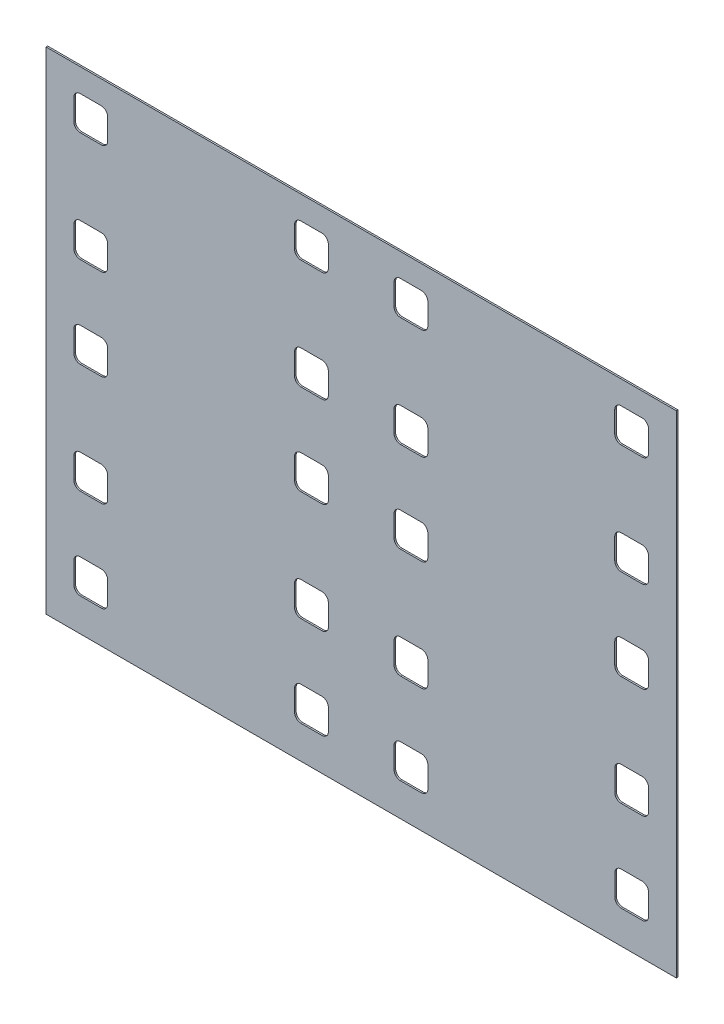
SolidWorks part; units mm, degrees
material "ABS"
ref_plane "X-Y Datum" through (0, 0, 0) normal (0, 0, 1) x (1, 0, 0)
ref_plane "X-Z Datum" through (0, 0, 0) normal (0, 1, 0) x (1, 0, 0)
ref_plane "Y-Z Datum" through (0, 0, 0) normal (1, 0, 0) x (0, 0, -1)
sketch "Sketch9" plane through (0, 0, 0) normal (0, 0, 1) x (1, 0, 0)
  line L0 (-83.6449, -183.2879) -> (-83.647, -162.6379) construction
  line L1 (-89.9977, -156.2885) -> (-110.6477, -156.2907) construction
  line L2 (-116.997, -162.6414) -> (-116.9949, -183.2914) construction
  line L3 (-110.6442, -189.6407) -> (-89.9942, -189.6385) construction
  line L4 (476.934, -311.4483) -> (476.8831, 172.8027)
  line L5 (476.8831, 172.8027) -> (-144.3755, 172.7375)
  line L6 (-144.3755, 172.7375) -> (-144.3246, -311.5135)
  line L7 (-144.3246, -311.5135) -> (476.934, -311.4483)
  line L8 (476.934, -311.4483) -> (476.8831, 172.8027)
  line L9 (476.8831, 172.8027) -> (-144.3755, 172.7375)
  line L10 (-144.3755, 172.7375) -> (-144.3246, -311.5135)
  line L11 (-144.3246, -311.5135) -> (476.934, -311.4483)
  line L12 (-110.6556, -81.3351) -> (-90.0056, -81.3329) construction
  line L13 (-83.6562, -74.9823) -> (-83.6584, -54.3323) construction
  line L14 (-90.0091, -47.9829) -> (-110.6591, -47.9851) construction
  line L15 (-117.0084, -54.3358) -> (-117.0062, -74.9858) construction
  line L16 (-83.677, 122.7313) -> (-83.6792, 143.3813) construction
  line L17 (-90.0298, 149.7307) -> (-110.6798, 149.7285) construction
  line L18 (-117.0292, 143.3778) -> (-117.027, 122.7278) construction
  line L19 (-110.6763, 116.3785) -> (-90.0263, 116.3807) construction
  line L20 (-110.665, 8.0729) -> (-90.015, 8.0751) construction
  line L21 (-117.0178, 35.0722) -> (-117.0156, 14.4222) construction
  line L22 (-90.0185, 41.4251) -> (-110.6685, 41.4229) construction
  line L23 (-83.6656, 14.4257) -> (-83.6678, 35.0757) construction
  line L24 (-83.6449, -183.2879) -> (-83.647, -162.6379)
  line L25 (-89.9977, -156.2885) -> (-110.6477, -156.2907)
  line L26 (-116.997, -162.6414) -> (-116.9949, -183.2914)
  line L27 (-110.6442, -189.6407) -> (-89.9942, -189.6385)
  line L28 (-110.6556, -81.3351) -> (-90.0056, -81.3329)
  line L29 (-83.6562, -74.9823) -> (-83.6584, -54.3323)
  line L30 (-90.0091, -47.9829) -> (-110.6591, -47.9851)
  line L31 (-117.0084, -54.3358) -> (-117.0062, -74.9858)
  line L32 (-83.677, 122.7313) -> (-83.6792, 143.3813)
  line L33 (-90.0298, 149.7307) -> (-110.6798, 149.7285)
  line L34 (-117.0292, 143.3778) -> (-117.027, 122.7278)
  line L35 (-110.6763, 116.3785) -> (-90.0263, 116.3807)
  line L36 (-110.665, 8.0729) -> (-90.015, 8.0751)
  line L37 (-117.0178, 35.0722) -> (-117.0156, 14.4222)
  line L38 (-90.0185, 41.4251) -> (-110.6685, 41.4229)
  line L39 (-83.6656, 14.4257) -> (-83.6678, 35.0757)
  line L40 (-83.6355, -272.6959) -> (-83.6376, -252.0459) construction
  line L41 (-89.9883, -245.6965) -> (-110.6383, -245.6987) construction
  line L42 (-116.9876, -252.0494) -> (-116.9855, -272.6994) construction
  line L43 (-110.6348, -279.0487) -> (-89.9848, -279.0465) construction
  line L44 (-83.6355, -272.6959) -> (-83.6376, -252.0459)
  line L45 (-89.9883, -245.6965) -> (-110.6383, -245.6987)
  line L46 (-116.9876, -252.0494) -> (-116.9855, -272.6994)
  line L47 (-110.6348, -279.0487) -> (-89.9848, -279.0465)
  arc A0 (-89.9942, -189.6385) -> (-83.6449, -183.2879) centre (-89.9949, -183.2885) ccw construction
  arc A1 (-83.647, -162.6379) -> (-89.9977, -156.2885) centre (-89.997, -162.6385) ccw construction
  arc A2 (-110.6477, -156.2907) -> (-116.997, -162.6414) centre (-110.647, -162.6407) ccw construction
  arc A3 (-116.9949, -183.2914) -> (-110.6442, -189.6407) centre (-110.6449, -183.2907) ccw construction
  arc A4 (-90.0056, -81.3329) -> (-83.6562, -74.9823) centre (-90.0062, -74.9829) ccw construction
  arc A5 (-83.6584, -54.3323) -> (-90.0091, -47.9829) centre (-90.0084, -54.3329) ccw construction
  arc A6 (-110.6591, -47.9851) -> (-117.0084, -54.3358) centre (-110.6584, -54.3351) ccw construction
  arc A7 (-117.0062, -74.9858) -> (-110.6556, -81.3351) centre (-110.6562, -74.9851) ccw construction
  arc A8 (-90.0263, 116.3807) -> (-83.677, 122.7313) centre (-90.027, 122.7307) ccw construction
  arc A9 (-83.6792, 143.3813) -> (-90.0298, 149.7307) centre (-90.0292, 143.3807) ccw construction
  arc A10 (-110.6798, 149.7285) -> (-117.0292, 143.3778) centre (-110.6792, 143.3785) ccw construction
  arc A11 (-117.027, 122.7278) -> (-110.6763, 116.3785) centre (-110.677, 122.7285) ccw construction
  arc A12 (-83.6678, 35.0757) -> (-90.0185, 41.4251) centre (-90.0178, 35.0751) ccw construction
  arc A13 (-90.015, 8.0751) -> (-83.6656, 14.4257) centre (-90.0156, 14.4251) ccw construction
  arc A14 (-117.0156, 14.4222) -> (-110.665, 8.0729) centre (-110.6656, 14.4229) ccw construction
  arc A15 (-110.6685, 41.4229) -> (-117.0178, 35.0722) centre (-110.6678, 35.0729) ccw construction
  arc A16 (-89.9942, -189.6385) -> (-83.6449, -183.2879) centre (-89.9949, -183.2885) ccw
  arc A17 (-83.647, -162.6379) -> (-89.9977, -156.2885) centre (-89.997, -162.6385) ccw
  arc A18 (-110.6477, -156.2907) -> (-116.997, -162.6414) centre (-110.647, -162.6407) ccw
  arc A19 (-116.9949, -183.2914) -> (-110.6442, -189.6407) centre (-110.6449, -183.2907) ccw
  arc A20 (-90.0056, -81.3329) -> (-83.6562, -74.9823) centre (-90.0062, -74.9829) ccw
  arc A21 (-83.6584, -54.3323) -> (-90.0091, -47.9829) centre (-90.0084, -54.3329) ccw
  arc A22 (-110.6591, -47.9851) -> (-117.0084, -54.3358) centre (-110.6584, -54.3351) ccw
  arc A23 (-117.0062, -74.9858) -> (-110.6556, -81.3351) centre (-110.6562, -74.9851) ccw
  arc A24 (-90.0263, 116.3807) -> (-83.677, 122.7313) centre (-90.027, 122.7307) ccw
  arc A25 (-83.6792, 143.3813) -> (-90.0298, 149.7307) centre (-90.0292, 143.3807) ccw
  arc A26 (-110.6798, 149.7285) -> (-117.0292, 143.3778) centre (-110.6792, 143.3785) ccw
  arc A27 (-117.027, 122.7278) -> (-110.6763, 116.3785) centre (-110.677, 122.7285) ccw
  arc A28 (-83.6678, 35.0757) -> (-90.0185, 41.4251) centre (-90.0178, 35.0751) ccw
  arc A29 (-90.015, 8.0751) -> (-83.6656, 14.4257) centre (-90.0156, 14.4251) ccw
  arc A30 (-117.0156, 14.4222) -> (-110.665, 8.0729) centre (-110.6656, 14.4229) ccw
  arc A31 (-110.6685, 41.4229) -> (-117.0178, 35.0722) centre (-110.6678, 35.0729) ccw
  arc A32 (-89.9848, -279.0465) -> (-83.6355, -272.6959) centre (-89.9855, -272.6965) ccw construction
  arc A33 (-110.6383, -245.6987) -> (-116.9876, -252.0494) centre (-110.6376, -252.0487) ccw construction
  arc A34 (-116.9855, -272.6994) -> (-110.6348, -279.0487) centre (-110.6355, -272.6987) ccw construction
  arc A35 (-89.9848, -279.0465) -> (-83.6355, -272.6959) centre (-89.9855, -272.6965) ccw
  arc A36 (-110.6383, -245.6987) -> (-116.9876, -252.0494) centre (-110.6376, -252.0487) ccw
  arc A37 (-116.9855, -272.6994) -> (-110.6348, -279.0487) centre (-110.6355, -272.6987) ccw
  arc A38 (-83.6376, -252.0459) -> (-89.9883, -245.6965) centre (-89.9876, -252.0465) ccw construction
  arc A39 (-83.6376, -252.0459) -> (-89.9883, -245.6965) centre (-89.9876, -252.0465) ccw
  dimension "D1" = 0
extrude "Boss-Extrude2" add sketch "Sketch9" along normal blind 1.5875 contours L10 L11 L8 L9 A39 L44 A35 L47 A37 L46 A36 L45 A31 L38 A28 L39 A29 L36 A30 L37 A27 L34 A26 L33 A25 L32 A24 L35 A23 L31 A22 L30 A21 L29 A20 L28 A19 L26 A18 L25 A17 L24 A16 L27 | L44 A39 L45 A36 L46 A37 L47 A35 | L26 A19 L27 A16 L24 A17 L25 A18 | L38 A31 L37 A30 L36 A29 L39 A28 | L34 A27 L35 A24 L32 A25 L33 A26 | L31 A23 L28 A20 L29 A21 L30 A22
sketch "Sketch10" plane through (0, 0, 1.5875) normal (0, 0, 1) x (1, 0, 0)
  line L4 (476.934, -311.4483) -> (476.8831, 172.8027)
  line L5 (476.8831, 172.8027) -> (-144.3755, 172.7375)
  line L6 (-144.3755, 172.7375) -> (-144.3246, -311.5135)
  line L7 (-144.3246, -311.5135) -> (476.934, -311.4483)
  line L8 (476.934, -311.4483) -> (476.8831, 172.8027)
  line L9 (476.8831, 172.8027) -> (-144.3755, 172.7375)
  line L10 (-144.3755, 172.7375) -> (-144.3246, -311.5135)
  line L11 (-144.3246, -311.5135) -> (476.934, -311.4483)
  line L12 (-116.997, -162.6414) -> (-116.9949, -183.2914)
  line L13 (-110.6442, -189.6407) -> (-89.9942, -189.6385)
  line L14 (-83.6449, -183.2879) -> (-83.647, -162.6379)
  line L15 (-89.9977, -156.2885) -> (-110.6477, -156.2907)
  line L16 (-116.997, -162.6414) -> (-116.9949, -183.2914)
  line L17 (-110.6442, -189.6407) -> (-89.9942, -189.6385)
  line L18 (-83.6449, -183.2879) -> (-83.647, -162.6379)
  line L19 (-89.9977, -156.2885) -> (-110.6477, -156.2907)
  line L20 (-116.9876, -252.0494) -> (-116.9855, -272.6994)
  line L21 (-89.9883, -245.6965) -> (-110.6383, -245.6987)
  line L22 (-83.6355, -272.6959) -> (-83.6376, -252.0459)
  line L23 (-110.6348, -279.0487) -> (-89.9848, -279.0465)
  line L24 (-116.9876, -252.0494) -> (-116.9855, -272.6994)
  line L25 (-89.9883, -245.6965) -> (-110.6383, -245.6987)
  line L26 (-83.6355, -272.6959) -> (-83.6376, -252.0459)
  line L27 (-110.6348, -279.0487) -> (-89.9848, -279.0465)
  line L28 (-90.0091, -47.9829) -> (-110.6591, -47.9851)
  line L29 (-117.0084, -54.3358) -> (-117.0062, -74.9858)
  line L30 (-110.6556, -81.3351) -> (-90.0056, -81.3329)
  line L31 (-83.6562, -74.9823) -> (-83.6584, -54.3323)
  line L32 (-90.0091, -47.9829) -> (-110.6591, -47.9851)
  line L33 (-117.0084, -54.3358) -> (-117.0062, -74.9858)
  line L34 (-110.6556, -81.3351) -> (-90.0056, -81.3329)
  line L35 (-83.6562, -74.9823) -> (-83.6584, -54.3323)
  line L36 (-83.677, 122.7313) -> (-83.6792, 143.3813)
  line L37 (-110.6763, 116.3785) -> (-90.0263, 116.3807)
  line L38 (-117.0292, 143.3778) -> (-117.027, 122.7278)
  line L39 (-90.0298, 149.7307) -> (-110.6798, 149.7285)
  line L40 (-83.677, 122.7313) -> (-83.6792, 143.3813)
  line L41 (-110.6763, 116.3785) -> (-90.0263, 116.3807)
  line L42 (-117.0292, 143.3778) -> (-117.027, 122.7278)
  line L43 (-90.0298, 149.7307) -> (-110.6798, 149.7285)
  line L44 (-110.665, 8.0729) -> (-90.015, 8.0751)
  line L45 (-83.6656, 14.4257) -> (-83.6678, 35.0757)
  line L46 (-90.0185, 41.4251) -> (-110.6685, 41.4229)
  line L47 (-117.0178, 35.0722) -> (-117.0156, 14.4222)
  line L48 (-110.665, 8.0729) -> (-90.015, 8.0751)
  line L49 (-83.6656, 14.4257) -> (-83.6678, 35.0757)
  line L50 (-90.0185, 41.4251) -> (-110.6685, 41.4229)
  line L51 (-117.0178, 35.0722) -> (-117.0156, 14.4222)
  arc A4 (-116.9949, -183.2914) -> (-110.6442, -189.6407) centre (-110.6449, -183.2907) ccw
  arc A5 (-89.9942, -189.6385) -> (-83.6449, -183.2879) centre (-89.9949, -183.2885) ccw
  arc A6 (-83.647, -162.6379) -> (-89.9977, -156.2885) centre (-89.997, -162.6385) ccw
  arc A7 (-110.6477, -156.2907) -> (-116.997, -162.6414) centre (-110.647, -162.6407) ccw
  arc A8 (-116.9949, -183.2914) -> (-110.6442, -189.6407) centre (-110.6449, -183.2907) ccw
  arc A9 (-89.9942, -189.6385) -> (-83.6449, -183.2879) centre (-89.9949, -183.2885) ccw
  arc A10 (-83.647, -162.6379) -> (-89.9977, -156.2885) centre (-89.997, -162.6385) ccw
  arc A11 (-110.6477, -156.2907) -> (-116.997, -162.6414) centre (-110.647, -162.6407) ccw
  arc A12 (-110.6383, -245.6987) -> (-116.9876, -252.0494) centre (-110.6376, -252.0487) ccw
  arc A13 (-83.6376, -252.0459) -> (-89.9883, -245.6965) centre (-89.9876, -252.0465) ccw
  arc A14 (-89.9848, -279.0465) -> (-83.6355, -272.6959) centre (-89.9855, -272.6965) ccw
  arc A15 (-116.9855, -272.6994) -> (-110.6348, -279.0487) centre (-110.6355, -272.6987) ccw
  arc A16 (-110.6383, -245.6987) -> (-116.9876, -252.0494) centre (-110.6376, -252.0487) ccw
  arc A17 (-83.6376, -252.0459) -> (-89.9883, -245.6965) centre (-89.9876, -252.0465) ccw
  arc A18 (-89.9848, -279.0465) -> (-83.6355, -272.6959) centre (-89.9855, -272.6965) ccw
  arc A19 (-116.9855, -272.6994) -> (-110.6348, -279.0487) centre (-110.6355, -272.6987) ccw
  arc A20 (-110.6591, -47.9851) -> (-117.0084, -54.3358) centre (-110.6584, -54.3351) ccw
  arc A21 (-117.0062, -74.9858) -> (-110.6556, -81.3351) centre (-110.6562, -74.9851) ccw
  arc A22 (-90.0056, -81.3329) -> (-83.6562, -74.9823) centre (-90.0062, -74.9829) ccw
  arc A23 (-83.6584, -54.3323) -> (-90.0091, -47.9829) centre (-90.0084, -54.3329) ccw
  arc A24 (-110.6591, -47.9851) -> (-117.0084, -54.3358) centre (-110.6584, -54.3351) ccw
  arc A25 (-117.0062, -74.9858) -> (-110.6556, -81.3351) centre (-110.6562, -74.9851) ccw
  arc A26 (-90.0056, -81.3329) -> (-83.6562, -74.9823) centre (-90.0062, -74.9829) ccw
  arc A27 (-83.6584, -54.3323) -> (-90.0091, -47.9829) centre (-90.0084, -54.3329) ccw
  arc A28 (-90.0263, 116.3807) -> (-83.677, 122.7313) centre (-90.027, 122.7307) ccw
  arc A29 (-117.027, 122.7278) -> (-110.6763, 116.3785) centre (-110.677, 122.7285) ccw
  arc A30 (-110.6798, 149.7285) -> (-117.0292, 143.3778) centre (-110.6792, 143.3785) ccw
  arc A31 (-83.6792, 143.3813) -> (-90.0298, 149.7307) centre (-90.0292, 143.3807) ccw
  arc A32 (-90.0263, 116.3807) -> (-83.677, 122.7313) centre (-90.027, 122.7307) ccw
  arc A33 (-117.027, 122.7278) -> (-110.6763, 116.3785) centre (-110.677, 122.7285) ccw
  arc A34 (-110.6798, 149.7285) -> (-117.0292, 143.3778) centre (-110.6792, 143.3785) ccw
  arc A35 (-83.6792, 143.3813) -> (-90.0298, 149.7307) centre (-90.0292, 143.3807) ccw
  arc A36 (-90.015, 8.0751) -> (-83.6656, 14.4257) centre (-90.0156, 14.4251) ccw
  arc A37 (-83.6678, 35.0757) -> (-90.0185, 41.4251) centre (-90.0178, 35.0751) ccw
  arc A38 (-110.6685, 41.4229) -> (-117.0178, 35.0722) centre (-110.6678, 35.0729) ccw
  arc A39 (-117.0156, 14.4222) -> (-110.665, 8.0729) centre (-110.6656, 14.4229) ccw
  arc A40 (-90.015, 8.0751) -> (-83.6656, 14.4257) centre (-90.0156, 14.4251) ccw
  arc A41 (-83.6678, 35.0757) -> (-90.0185, 41.4251) centre (-90.0178, 35.0751) ccw
  arc A42 (-110.6685, 41.4229) -> (-117.0178, 35.0722) centre (-110.6678, 35.0729) ccw
  arc A43 (-117.0156, 14.4222) -> (-110.665, 8.0729) centre (-110.6656, 14.4229) ccw
  dimension "D1" = 0
  dimension "D2" = 0
  dimension "D3" = 0
  dimension "D4" = 0
  dimension "D5" = 0
  dimension "D6" = 0
extrude "Cut-Extrude6" cut sketch "Sketch10" against normal through all contours L40 A35 L43 A34 L42 A33 L41 A32 | L51 A43 L48 A40 L49 A41 L50 A42 | L35 A27 L32 A24 L33 A25 L34 A26 | L19 A11 L16 A8 L17 A9 L18 A10 | L24 A19 L27 A18 L26 A17 L25 A16
pattern_linear "LPattern2" count 2 spacing 217.5764 along (1, 0.0001, 0) of "Cut-Extrude6"
ref_plane "Plane1" through (166.272, 0.0175, 0) normal (-1, -0.0001, 0) x (0, 0, 1)
mirror "Mirror1" about plane through (166.272, 0.0175, 0) normal (-1, -0.0001, 0) of "LPattern2", "Cut-Extrude6"
